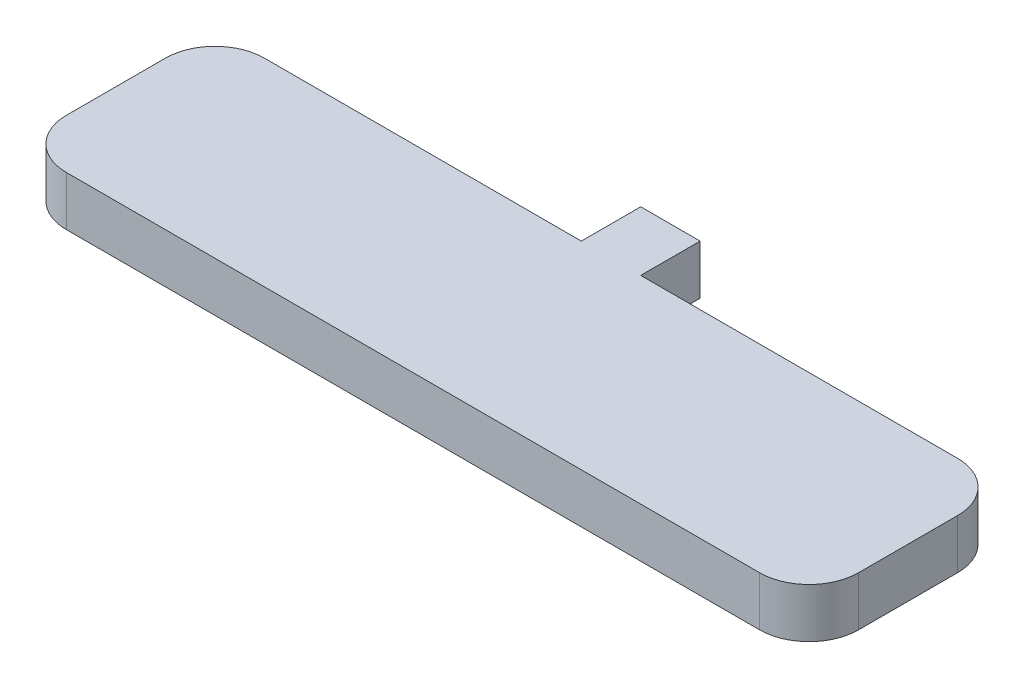
SolidWorks part; units mm, degrees
ref_plane "Front Plane" through (0, 0, 0) normal (0, 0, 1) x (1, 0, 0)
ref_plane "Top Plane" through (0, 0, 0) normal (0, 1, 0) x (1, 0, 0)
ref_plane "Right Plane" through (0, 0, 0) normal (1, 0, 0) x (0, 0, -1)
sketch "Sketch1" plane through (0, 0, 0) normal (0, 1, 0) x (1, 0, 0)
  line L0 (0, 38.995) -> (0, -42.0101) construction
  line L1 (-40, 10) -> (40, 10)
  line L2 (-40, 10) -> (-40, -10)
  line L3 (-40, -10) -> (40, -10)
  line L4 (40, 10) -> (40, -10)
  line L5 (-40, 10) -> (40, -10) construction
  line L6 (-40, -10) -> (40, 10) construction
  line L7 (-54.8744, 0) -> (60.1005, 0) construction
  point P0 (0, 0)
  dimension "D1" = 80
  dimension "D2" = 20
extrude "Boss-Extrude1" add sketch "Sketch1" along normal blind 5
fillet "Fillet1" radius 5 4 edges at (-40, 2.5, -10) (-40, 2.5, 10) (40, 2.5, -10) (40, 2.5, 10)
shell "Shell1" thickness 2
sketch "Sketch2" plane through (0, 0, -10) normal (0, 0, -1) x (-1, 0, 0)
  line L0 (0, 0) -> (-3, 0) construction
  line L1 (0, 25.82) -> (0, -15.5481) construction
  line L7 (35, 5) -> (-35, 5) construction
  line L8 (3, 5) -> (-3, 5)
  line L9 (3, 5) -> (3, 0)
  line L10 (35, 0) -> (-35, 0) construction
  line L11 (-3, 5) -> (-3, 0)
  line L12 (3, 0) -> (-3, 0)
  dimension "D1" = 6
extrude "Boss-Extrude2" add sketch "Sketch2" along normal blind 6
sketch "Sketch3" plane through (0, 0, -16) normal (0, 0, -1) x (-1, 0, 0)
  line L0 (0, 5) -> (0, 0) construction
  line L2 (-3, 0) -> (3, 0) construction
  line L3 (3, 5) -> (-3, 5) construction
  circle A0 centre (0, 2.5) radius 1.425
  point P5 (0, 5)
  point P9 (0, 0)
  dimension "D1" = 2.85
extrude "Cut-Extrude1" cut sketch "Sketch3" against normal blind 4
